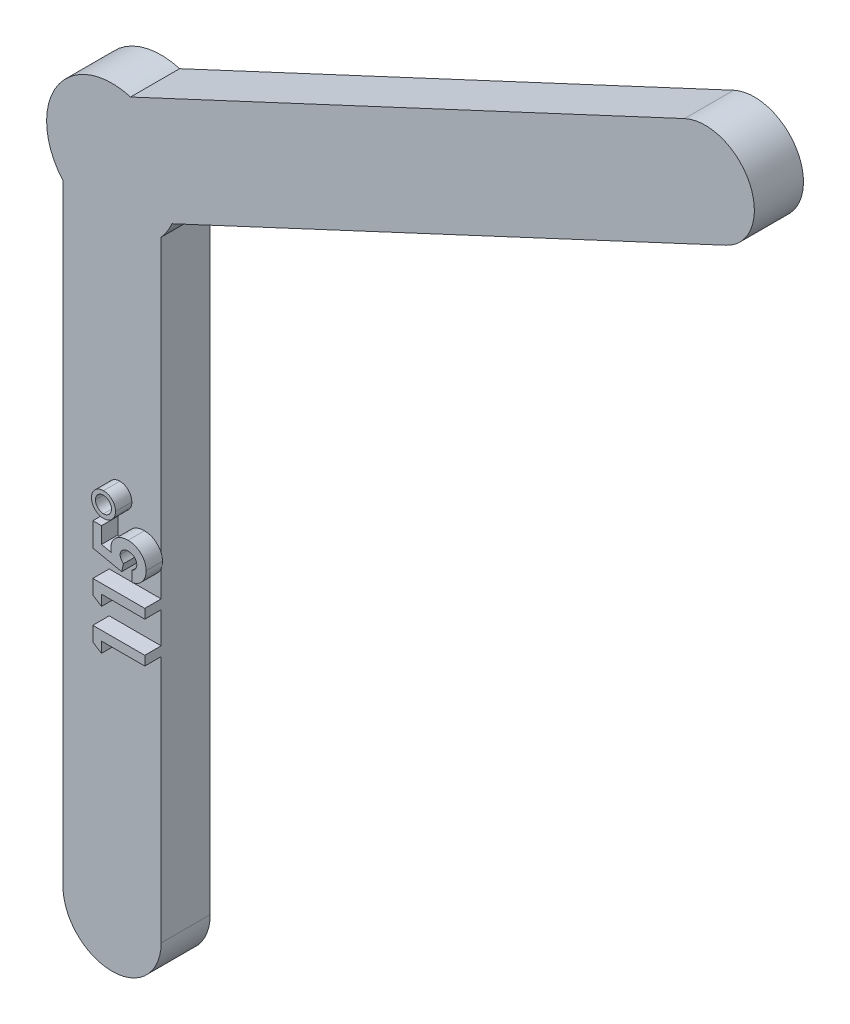
SolidWorks part; units mm, degrees
ref_plane "Front Plane" through (0, 0, 0) normal (0, 0, 1) x (1, 0, 0)
ref_plane "Top Plane" through (0, 0, 0) normal (0, 1, 0) x (1, 0, 0)
ref_plane "Right Plane" through (0, 0, 0) normal (1, 0, 0) x (0, 0, -1)
sketch "Sketch2" plane through (0, 0, 0) normal (0, 0, 1) x (1, 0, 0)
  line L0 (0, 0) -> (0, -40) construction
  line L1 (0, 0) -> (36.2523, 16.9047) construction
  line L2 (34.9845, 19.6237) -> (37.5202, 14.1858) construction
  line L3 (-3, -40) -> (3, -40) construction
  line L4 (-3, -40) -> (-3, -2.6458)
  line L5 (3, -40) -> (3, -2.6458)
  line L6 (34.9845, 19.6237) -> (1.13, 3.8371)
  line L7 (37.5202, 14.1858) -> (3.6657, -1.6008)
  arc A0 (1.13, 3.8371) -> (-3, -2.6458) centre (0, 0) ccw
  arc A1 (-3, -40) -> (3, -40) centre (0, -40) ccw
  arc A2 (34.9845, 19.6237) -> (37.5202, 14.1858) centre (36.2523, 16.9047) cw
  arc A3 (3, -2.6458) -> (3.6657, -1.6008) centre (0, 0) ccw
  point P12 (36.2523, 16.9047)
  dimension "D3" = 3
  dimension "D4" = 8
  dimension "D1" = 40
  dimension "D2" = 115
extrude "Boss-Extrude1" add sketch "Sketch2" along normal blind 3 contours A0 L4 A1 L5 A3 L7 A2 L6
sketch "Sketch3" plane through (0, 0, 3) normal (0, 0, 1) x (1, 0, 0)
  text T0 "<b>115°</b>"
extrude "Boss-Extrude2" add sketch "Sketch3" along normal blind 1
